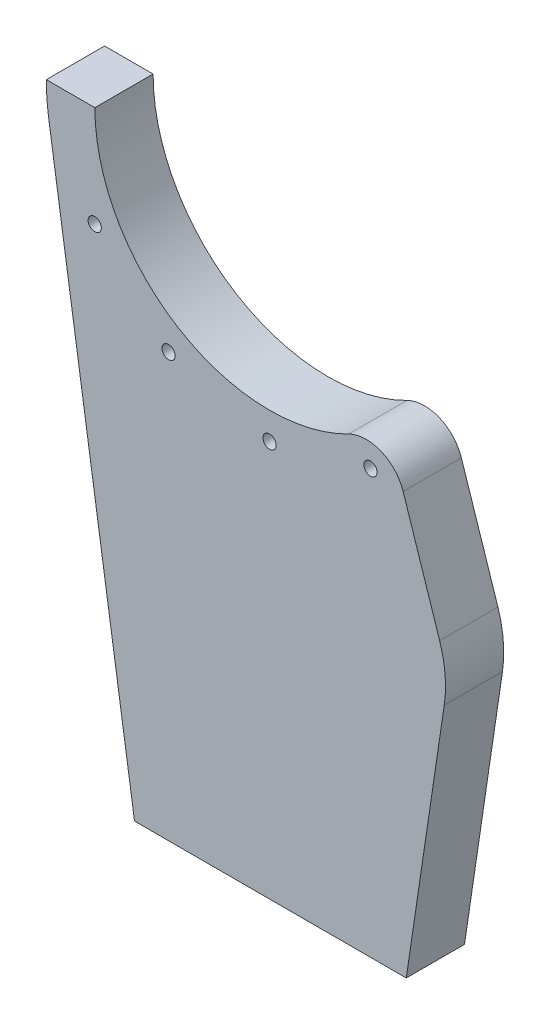
SolidWorks part; units mm, degrees
ref_plane "Front Plane" through (0, 0, 0) normal (0, 0, 1) x (1, 0, 0)
ref_plane "Top Plane" through (0, 0, 0) normal (0, 1, 0) x (1, 0, 0)
ref_plane "Right Plane" through (0, 0, 0) normal (1, 0, 0) x (0, 0, -1)
sketch "Sketch1" plane through (0, 0, 0) normal (0, 0, 1) x (1, 0, 0)
  line L0 (-57.5, 0) -> (-45, 0)
  line L1 (52, 0) -> (57.5, 0)
  line L2 (-56.8494, -8.625) -> (-34.7864, -154.0477)
  line L3 (46.0438, -81.2547) -> (35.2136, -154.0477)
  line L4 (-34.7864, -154.0477) -> (35.2136, -154.0477)
  line L5 (30.2586, -33.3079) -> (46.0438, -81.2547)
  arc A0 (-57.5, 0) -> (-56.8494, -8.625) centre (0, 0) ccw
  arc A1 (-45, 0) -> (30.2586, -33.3079) centre (0, 0) ccw
  arc A3 (-52, 0) -> (32.6241, -40.4928) centre (0, 0) ccw construction
  arc A6 (-52, 0) -> (32.6241, -40.4928) centre (0, 0) ccw construction
  arc A8 (-52, 0) -> (0, -52) centre (0, 0) ccw construction
  circle A13 centre (0, -52) radius 1.7
  circle A14 centre (-26, -45.0333) radius 1.7
  circle A15 centre (-45.0333, -26) radius 1.7
  circle A24 centre (26, -45.0333) radius 1.7
  circle A25 centre (-45.0333, 26) radius 1.7 [skipped]
  circle A26 centre (-26, 45.0333) radius 1.7 [skipped]
  circle A27 centre (0, 52) radius 1.7 [skipped]
  circle A28 centre (45.0333, 26) radius 1.7 [skipped]
  circle A29 centre (26, 45.0333) radius 1.7 [skipped]
  arc A30 (-51.9722, -1.6998) -> (-50.3, 0) centre (-52, 0) ccw [skipped]
  arc A31 (50.3, 0) -> (51.9722, -1.6998) centre (52, 0) ccw [skipped]
  arc A32 (56.874, -8.4618) -> (57.5, 0) centre (0, 0) ccw
  circle A33 centre (45.0333, -26) radius 1.7 [skipped]
  point P26 (0, 0)
  point P32 (0, 0)
  point P50 (0, 0)
  dimension "D1" = 90
  dimension "D2" = 115
  dimension "D3" = 70
  dimension "D5" = 104
  dimension "D6" = 3.4
  dimension "D7" = 3
  dimension "D8" = 12
extrude "Boss-Extrude1" add sketch "Sketch1" along normal blind 15
fillet "Fillet1" radius 10 1 edges at (30.2586, -33.3079, 7.5)
fillet "Fillet2" radius 30 1 edges at (46.0438, -81.2547, 7.5)
